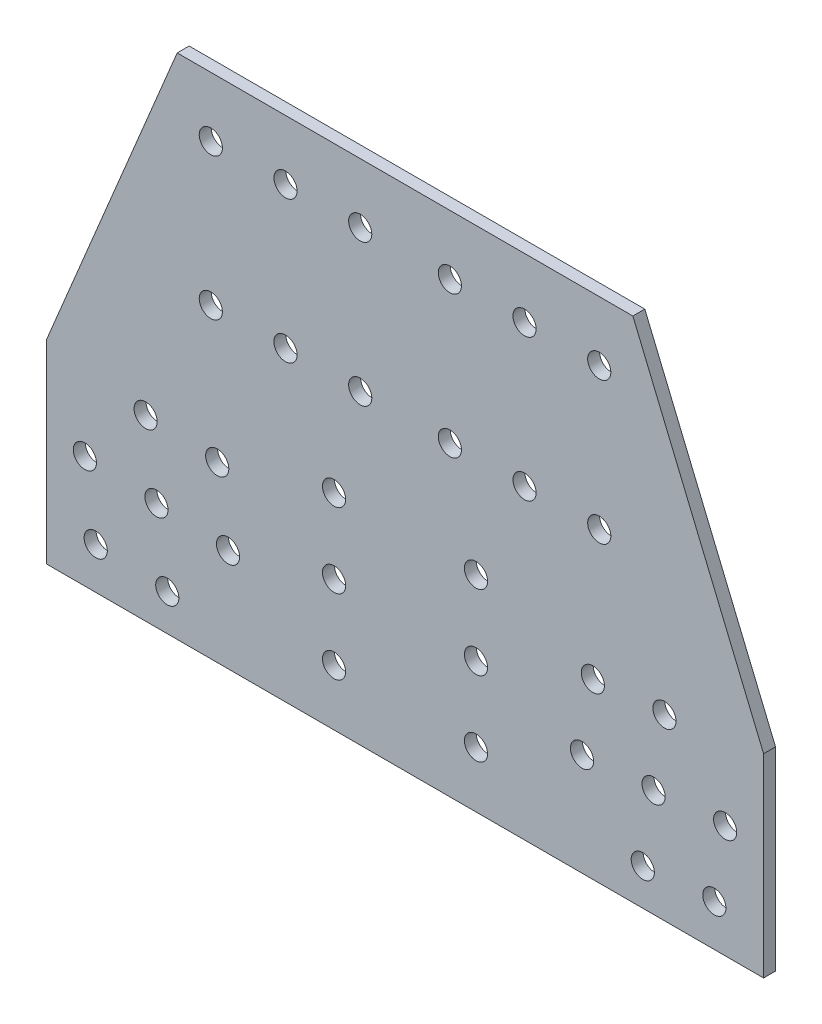
SolidWorks part; units mm, degrees
ref_plane "前视基准面" through (0, 0, 0) normal (0, 0, 1) x (1, 0, 0)
ref_plane "上视基准面" through (0, 0, 0) normal (0, 1, 0) x (1, 0, 0)
ref_plane "右视基准面" through (0, 0, 0) normal (1, 0, 0) x (0, 0, -1)
sketch "草图1" plane through (0, 0, 0) normal (0, 0, 1) x (1, 0, 0)
  line L0 (388.3254, -574.544) -> (388.3254, 49425.456) construction
  line L1 (693.3254, 420) -> (83.3254, 420)
  line L2 (693.3254, 420) -> (868.3254, 0)
  line L3 (868.3254, 0) -> (868.3254, -260)
  line L4 (-91.6746, 0) -> (-91.6746, -260)
  line L5 (-91.6746, -260) -> (868.3254, -260)
  line L6 (83.3254, 420) -> (-91.6746, 0)
  point P8 (388.3254, -260)
  point P10 (388.3254, 420)
  dimension "D2" = 175
  dimension "D1" = 680
  dimension "D3" = 388.3254
  dimension "D4" = 260
extrude "拉伸2" add sketch "草图1" along normal blind 16 contours L1 L6 L4 L5 L3 L2
sketch "草图2" plane through (0, 0, 16) normal (0, 0, 1) x (1, 0, 0)
  line L0 (388.3254, -1260) -> (388.3254, 48740) construction
  line L1 (-91.6746, -260) -> (868.3254, -260) construction
  line L2 (-1146.8947, 245) -> (48853.1053, 245) construction
  line L4 (679.8014, -154.0924) -> (766.0445, -74.6056) construction
  line L5 (693.3254, 420) -> (83.3254, 420) construction
  line L6 (4388.3254, -4095) -> (388.3254, -4095) construction
  line L7 (388.3254, 245) -> (4388.3254, -4095) construction
  line L8 (388.3254, 245) -> (4388.3254, -4095) construction
  circle A0 centre (328.3254, 340) radius 15.5
  circle A1 centre (228.3254, 340) radius 15.5
  circle A2 centre (128.3254, 340) radius 15.5
  circle A3 centre (128.3254, 150) radius 15.5
  circle A4 centre (228.3254, 150) radius 15.5
  circle A5 centre (328.3254, 150) radius 15.5
  circle A6 centre (293.3254, -185) radius 15.5
  circle A7 centre (293.3254, 15) radius 15.5
  circle A8 centre (293.3254, -85) radius 15.5
  circle A9 centre (639.7583, -27.8048) radius 15.5
  circle A10 centre (721.0844, -116.0435) radius 15.5
  circle A11 centre (802.4104, -204.2823) radius 15.5
  circle A12 centre (735.5706, -21.0954) radius 15.5
  circle A13 centre (706.5982, -210.9917) radius 15.5
  circle A14 centre (625.2721, -122.7529) radius 15.5
  circle A15 centre (816.8966, -109.3341) radius 15.5
  circle A16 centre (151.3786, -122.7529) radius 15.5
  circle A17 centre (70.0525, -210.9917) radius 15.5
  circle A18 centre (-25.7597, -204.2823) radius 15.5
  circle A19 centre (55.5663, -116.0435) radius 15.5
  circle A20 centre (136.8924, -27.8048) radius 15.5
  circle A21 centre (-40.2459, -109.3341) radius 15.5
  circle A22 centre (41.0801, -21.0954) radius 15.5
  circle A23 centre (448.3254, 150) radius 15.5
  circle A24 centre (548.3254, 150) radius 15.5
  circle A25 centre (648.3254, 150) radius 15.5
  circle A26 centre (648.3254, 340) radius 15.5
  circle A27 centre (548.3254, 340) radius 15.5
  circle A28 centre (448.3254, 340) radius 15.5
  circle A29 centre (483.3254, -85) radius 15.5
  circle A30 centre (483.3254, 15) radius 15.5
  circle A31 centre (483.3254, -185) radius 15.5
  point P5 (388.3254, -260)
  dimension "D1" = 31
  dimension "D4" = 31
  dimension "D6" = 31
  dimension "D9" = 31
  dimension "D12" = 31
  dimension "D14" = 31
  dimension "D17" = 31
  dimension "D19" = 31
  dimension "D21" = 31
  dimension "D25" = 31
  dimension "D26" = 4000
  dimension "D2" = 60
  dimension "D3" = 80
  dimension "D5" = 100
  dimension "D7" = 100
  dimension "D8" = 95
  dimension "D10" = 95
  dimension "D11" = 75
  dimension "D13" = 200
  dimension "D15" = 100
  dimension "D16" = 371
  dimension "D18" = 175
  dimension "D20" = 120
  dimension "D22" = 120
  dimension "D24" = 60
  dimension "D27" = 4340
  dimension "D28" = 75
extrude "拉伸3" cut sketch "草图2" against normal through all
